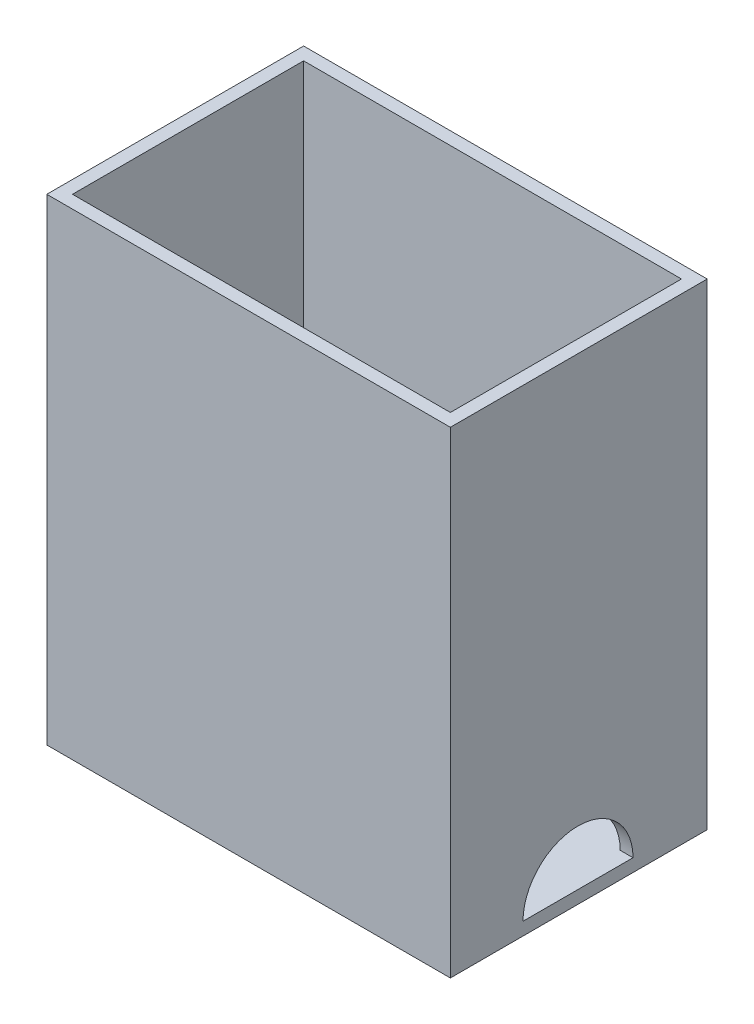
SolidWorks part; units mm, degrees
ref_plane "Alzado" through (0, 0, 0) normal (0, 0, 1) x (1, 0, 0)
ref_plane "Planta" through (0, 0, 0) normal (0, 1, 0) x (1, 0, 0)
ref_plane "Vista lateral" through (0, 0, 0) normal (1, 0, 0) x (0, 0, -1)
sketch "Croquis1" plane through (0, 0, 0) normal (0, 1, 0) x (1, 0, 0)
  line L1 (55, -35) -> (-55, -35)
  line L2 (55, -35) -> (55, 35)
  line L3 (55, 35) -> (-55, 35)
  line L4 (-55, -35) -> (-55, 35)
  line L5 (55, -35) -> (-55, 35) construction
  line L6 (55, 35) -> (-55, -35) construction
  point P0 (0, 0)
  dimension "D1" = 110
  dimension "D2" = 70
extrude "Saliente-Extruir3" add sketch "Croquis1" along normal blind 130
shell "Vaciado4" thickness 3.5
sketch "Croquis2" plane through (0, 0, 0) normal (0, 1, 0) x (1, 0, 0)
  circle A0 centre (-24.5, 0) radius 6
  circle A1 centre (24.5, 0) radius 6
  circle A2 centre (0, 0) radius 1.5
  point P6 (30.5, 0)
extrude "Cortar-Extruir4" cut sketch "Croquis2" along normal up to next
sketch "Croquis3" plane through (55, 0, 0) normal (1, 0, 0) x (0, 0, -1)
  line L0 (-15.2127, 3.5) -> (14.7838, 3.5)
  line L1 (-35, 0) -> (35, 0) construction
  arc A0 (-0.2145, 18.4983) -> (-15.2127, 3.5) centre (-0.2145, 3.5) ccw
  arc A1 (-0.2145, 18.4983) -> (14.7838, 3.5) centre (-0.2145, 3.5) cw
  point P0 (0, 0)
  point P1 (0, 2)
  point P5 (-15.2127, 3.5)
  point P6 (0, 2)
  point P7 (-0.2145, 18.4983)
  point P8 (14.7838, 3.5)
  dimension "D1" = 3.5
extrude "Cortar-Extruir8" cut sketch "Croquis3" against normal through all both and the other way through all
